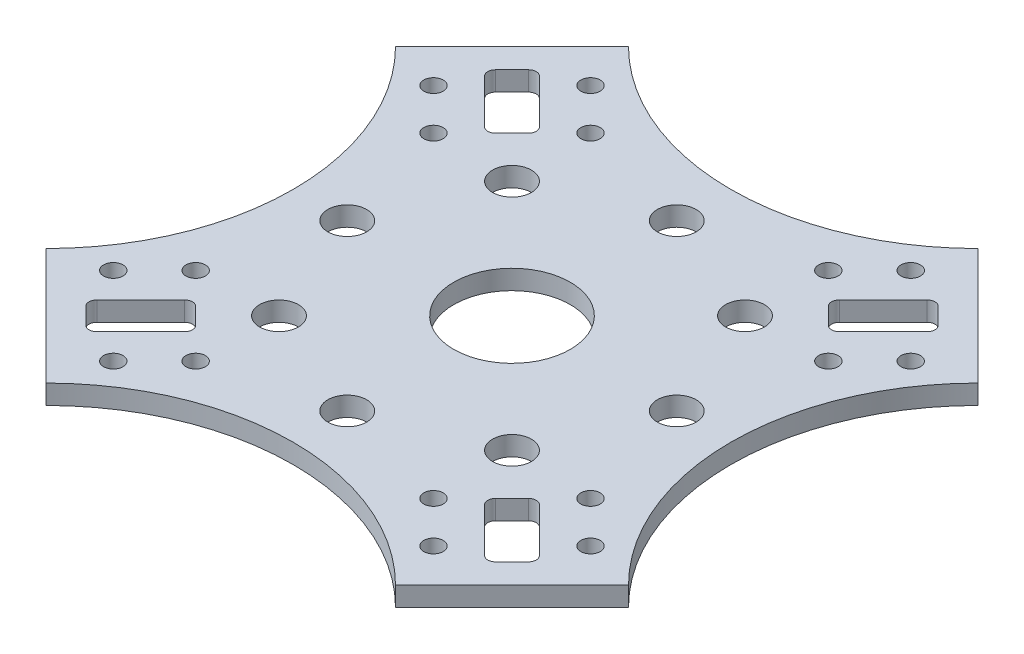
SolidWorks part; units mm, degrees
ref_plane "Front Plane" through (0, 0, 0) normal (0, 0, 1) x (1, 0, 0)
ref_plane "Top Plane" through (0, 0, 0) normal (0, 1, 0) x (1, 0, 0)
ref_plane "Right Plane" through (0, 0, 0) normal (1, 0, 0) x (0, 0, -1)
sketch "Sketch2" plane through (0, 0, 0) normal (0, 1, 0) x (1, 0, 0)
  line L0 (45, 75) -> (75, 45)
  line L5 (38.6102, 42.8529) -> (42.8529, 38.6102)
  line L6 (45.6813, 38.6102) -> (56.995, 49.924)
  line L7 (45, -75) -> (75, -45)
  line L8 (-75, -45) -> (-45, -75)
  line L9 (-75, 45) -> (-45, 75)
  line L10 (-120, 0) -> (120, 0) construction
  line L11 (0, -120) -> (0, 120) construction
  line L12 (0, 0) -> (60, 60) construction
  line L13 (56.995, 52.7524) -> (52.7524, 56.995)
  line L14 (38.6102, 45.6813) -> (49.924, 56.995)
  line L15 (45.6813, -38.6102) -> (56.995, -49.924)
  line L16 (52.7524, -56.995) -> (56.995, -52.7524)
  line L17 (38.6102, -45.6813) -> (49.924, -56.995)
  line L18 (42.8529, -38.6102) -> (38.6102, -42.8529)
  line L19 (-38.6102, -45.6813) -> (-49.924, -56.995)
  line L20 (-56.995, -52.7524) -> (-52.7524, -56.995)
  line L21 (-45.6813, -38.6102) -> (-56.995, -49.924)
  line L22 (-38.6102, -42.8529) -> (-42.8529, -38.6102)
  line L23 (-45.6813, 38.6102) -> (-56.995, 49.924)
  line L24 (-52.7524, 56.995) -> (-56.995, 52.7524)
  line L25 (-38.6102, 45.6813) -> (-49.924, 56.995)
  line L26 (-42.8529, 38.6102) -> (-38.6102, 42.8529)
  line L27 (51.3382, 44.2671) -> (64.4872, 31.118) construction
  line L28 (44.2671, 51.3382) -> (31.118, 64.4872) construction
  line L29 (37.6926, 57.9127) -> (30.6215, 50.8416) construction
  line L30 (37.6926, 57.9127) -> (41.2281, 61.4482) construction
  arc A0 (-45, 75) -> (45, 75) centre (0, 120) ccw
  arc A1 (-75, 45) -> (-75, -45) centre (-120, 0) cw
  arc A2 (75, 45) -> (75, -45) centre (120, 0) ccw
  arc A3 (-45, -75) -> (45, -75) centre (0, -120) cw
  circle A4 centre (0, 0) radius 15
  circle A5 centre (30, 30) radius 5
  circle A6 centre (42.4264, 0) radius 5
  circle A7 centre (30, -30) radius 5
  circle A8 centre (0, -42.4264) radius 5
  circle A9 centre (-30, -30) radius 5
  circle A10 centre (-42.4264, 0) radius 5
  circle A11 centre (-30, 30) radius 5
  circle A12 centre (0, 42.4264) radius 5
  arc A13 (42.8529, 38.6102) -> (45.6813, 38.6102) centre (44.2671, 40.0245) ccw
  arc A14 (56.995, 49.924) -> (56.995, 52.7524) centre (55.5808, 51.3382) ccw
  arc A15 (38.6102, 42.8529) -> (38.6102, 45.6813) centre (40.0245, 44.2671) cw
  arc A16 (49.924, 56.995) -> (52.7524, 56.995) centre (51.3382, 55.5808) cw
  arc A17 (56.995, -49.924) -> (56.995, -52.7524) centre (55.5808, -51.3382) cw
  arc A18 (49.924, -56.995) -> (52.7524, -56.995) centre (51.3382, -55.5808) ccw
  arc A19 (38.6102, -42.8529) -> (38.6102, -45.6813) centre (40.0245, -44.2671) ccw
  arc A20 (42.8529, -38.6102) -> (45.6813, -38.6102) centre (44.2671, -40.0245) cw
  arc A21 (-49.924, -56.995) -> (-52.7524, -56.995) centre (-51.3382, -55.5808) cw
  arc A22 (-56.995, -49.924) -> (-56.995, -52.7524) centre (-55.5808, -51.3382) ccw
  arc A23 (-42.8529, -38.6102) -> (-45.6813, -38.6102) centre (-44.2671, -40.0245) ccw
  arc A24 (-38.6102, -42.8529) -> (-38.6102, -45.6813) centre (-40.0245, -44.2671) cw
  arc A25 (-56.995, 49.924) -> (-56.995, 52.7524) centre (-55.5808, 51.3382) cw
  arc A26 (-49.924, 56.995) -> (-52.7524, 56.995) centre (-51.3382, 55.5808) ccw
  arc A27 (-38.6102, 42.8529) -> (-38.6102, 45.6813) centre (-40.0245, 44.2671) ccw
  arc A28 (-42.8529, 38.6102) -> (-45.6813, 38.6102) centre (-44.2671, 40.0245) cw
  circle A29 centre (41.2281, 61.4482) radius 2.5
  circle A30 centre (30.6215, 50.8416) radius 2.5
  circle A31 centre (61.4482, 41.2281) radius 2.5
  circle A32 centre (50.8416, 30.6215) radius 2.5
  circle A33 centre (61.4482, -41.2281) radius 2.5
  circle A34 centre (50.8416, -30.6215) radius 2.5
  circle A35 centre (41.2281, -61.4482) radius 2.5
  circle A36 centre (30.6215, -50.8416) radius 2.5
  circle A37 centre (-41.2281, -61.4482) radius 2.5
  circle A38 centre (-30.6215, -50.8416) radius 2.5
  circle A39 centre (-61.4482, -41.2281) radius 2.5
  circle A40 centre (-50.8416, -30.6215) radius 2.5
  circle A41 centre (-61.4482, 41.2281) radius 2.5
  circle A42 centre (-50.8416, 30.6215) radius 2.5
  circle A43 centre (-41.2281, 61.4482) radius 2.5
  circle A44 centre (-30.6215, 50.8416) radius 2.5
  point P0 (0, 0)
  point P35 (0, 0)
  point P42 (44.2671, 37.196)
  point P45 (58.4092, 51.3382)
  point P50 (40.7316, 40.7316)
  point P52 (54.8737, 54.8737)
  point P89 (0, 0)
  point P127 (0, 0)
  dimension "D2" = 10
  dimension "D1" = 30
  dimension "D6" = 2
  dimension "D10" = 5
  dimension "D11" = 5
  dimension "D4" = 5
  dimension "D5" = 20
  dimension "D8" = 10
  dimension "D9" = 5
  dimension "D3" = 8
  dimension "D7" = 4
  dimension "D12" = 4
extrude "Boss-Extrude1" add sketch "Sketch2" against normal blind 5
